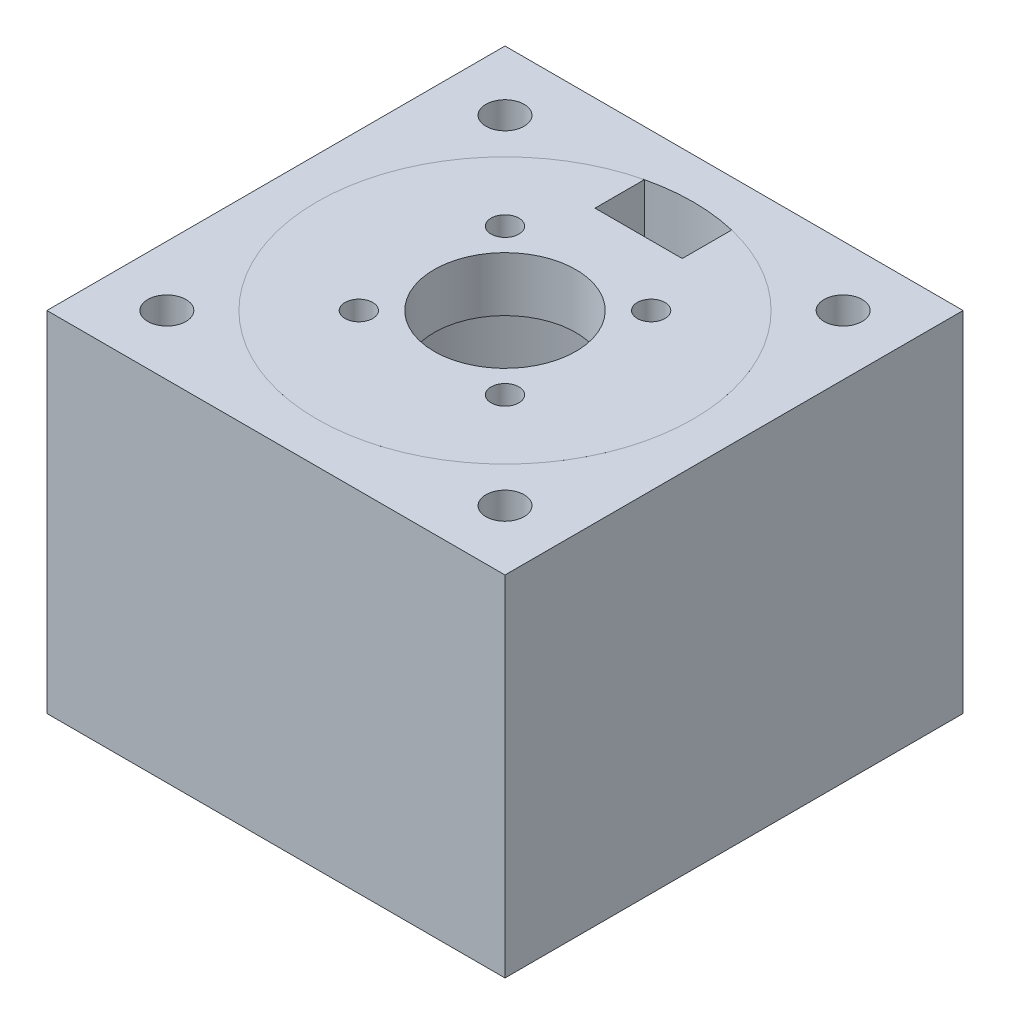
SolidWorks part; units mm, degrees
ref_plane "前视基准面" through (0, 0, 0) normal (0, 0, 1) x (1, 0, 0)
ref_plane "上视基准面" through (0, 0, 0) normal (0, 1, 0) x (1, 0, 0)
ref_plane "右视基准面" through (0, 0, 0) normal (1, 0, 0) x (0, 0, -1)
other "Configuration Table"
sketch "草图1" plane through (0, 0, 0) normal (0, 1, 0) x (1, 0, 0)
  line L0 (-42.7744, 0) -> (40.5419, 0) construction
  line L1 (0, 41.2812) -> (0, -32.3667) construction
  line L2 (-6.7, 41.2812) -> (-6.7, -32.3667) construction
  line L3 (6.7, 41.2812) -> (6.7, -32.3667) construction
  line L4 (-42.7744, -6.7) -> (40.5419, -6.7) construction
  line L5 (0, 41.2812) -> (0, -32.3667) construction
  line L6 (-42.7744, 6.7) -> (40.5419, 6.7) construction
  line L7 (0, 41.2812) -> (0, -32.3667) construction
  line L9 (-4, 22.25) -> (4, 22.25)
  line L10 (-4, 22.25) -> (-4, 12.25)
  line L11 (-4, 12.25) -> (4, 12.25)
  line L12 (4, 22.25) -> (4, 12.25)
  line L13 (-4, 22.25) -> (4, 12.25) construction
  line L14 (-4, 12.25) -> (4, 22.25) construction
  circle A0 centre (0, 0) radius 17.25
  circle A2 centre (-6.7, 6.7) radius 1.275
  circle A3 centre (6.7, 6.7) radius 1.275
  circle A4 centre (6.7, -6.7) radius 1.275
  circle A5 centre (-6.7, -6.7) radius 1.275
  circle A6 centre (0, 0) radius 6.5
  point P18 (0, 17.25)
  dimension "D1" = 34.5
  dimension "D6" = 2.55
  dimension "D9" = 13
  dimension "D2" = 6.7
  dimension "D3" = 6.7
  dimension "D7" = 10
  dimension "D8" = 8
  dimension "D4" = 6.7
  dimension "D5" = 6.7
extrude "凸台-拉伸1" add sketch "草图1" along normal blind 5 contours L10 A0 L12 L11 A3 A2 A4 A5
sketch "草图2" plane through (0, 0, 0) normal (0, -1, 0) x (1, 0, 0)
  line L0 (0, 60.9744) -> (0, -74.4705) construction
  line L1 (-76.6995, 0) -> (71.2326, 0) construction
  line L2 (-76.6995, -21) -> (71.2326, -21)
  line L3 (-76.6995, 21) -> (71.2326, 21)
  line L4 (-21, 60.9744) -> (-21, -74.4705)
  line L5 (21, 60.9744) -> (21, -74.4705)
  line L6 (-15.5, 60.9744) -> (-15.5, -74.4705) construction
  line L7 (15.5, 60.9744) -> (15.5, -74.4705) construction
  line L8 (-76.6995, -15.5) -> (71.2326, -15.5) construction
  line L9 (-76.6995, 15.5) -> (71.2326, 15.5) construction
  circle A0 centre (-15.5, 15.5) radius 1.75
  circle A1 centre (15.5, 15.5) radius 1.75
  circle A2 centre (15.5, -15.5) radius 1.75
  circle A3 centre (-15.5, -15.5) radius 1.75
  circle A4 centre (0, 0) radius 17.5
  arc A5 (4, -16.7798) -> (-4, -16.7798) centre (0, 0) ccw construction
  arc A6 (4, -16.7798) -> (-4, -16.7798) centre (0, 0) ccw
  line M10 (-4, -16.7798) -> (-4, -12.25)
  line M11 (-4, -12.25) -> (4, -12.25)
  line M12 (4, -12.25) -> (4, -16.7798)
  arc M13 (4, -16.7798) -> (-4, -16.7798) centre (0, 0) ccw
  dimension "D9" = 3.5
  dimension "D10" = 35
  dimension "D1" = 21
  dimension "D2" = 21
  dimension "D3" = 21
  dimension "D4" = 21
  dimension "D5" = 15.5
  dimension "D6" = 15.5
  dimension "D7" = 15.5
  dimension "D8" = 15.5
extrude "凸台-拉伸2" add sketch "草图2" along normal blind 27 separate body contours L5 L3 L4 L2 A1 A0 A2 A3 M10 M13 M12 M11
sketch "草图3" plane through (0, 0, 0) normal (0, 1, 0) x (1, 0, 0)
  line L0 (-21, -60.9744) -> (-21, 74.4705) construction
  line L1 (-76.6995, -21) -> (71.2326, -21) construction
  line L2 (21, -60.9744) -> (21, 74.4705) construction
  line L3 (-76.6995, 21) -> (71.2326, 21) construction
  line L4 (-21, -60.9744) -> (-21, 74.4705)
  line L5 (-76.6995, -21) -> (71.2326, -21)
  line L6 (21, -60.9744) -> (21, 74.4705)
  line L7 (-76.6995, 21) -> (71.2326, 21)
  circle A2 centre (0, 0) radius 17.25
  circle A3 centre (-15.5, -15.5) radius 1.75 construction
  circle A4 centre (15.5, -15.5) radius 1.75 construction
  circle A5 centre (15.5, 15.5) radius 1.75 construction
  circle A6 centre (-15.5, 15.5) radius 1.75 construction
  circle A7 centre (-15.5, -15.5) radius 1.75
  circle A8 centre (15.5, -15.5) radius 1.75
  circle A9 centre (15.5, 15.5) radius 1.75
  circle A10 centre (-15.5, 15.5) radius 1.75
  circle M2 centre (0, 0) radius 17.5
  circle M3 centre (15.5, -15.5) radius 1.75
  circle M4 centre (-15.5, -15.5) radius 1.75
  line M5 (21, -21) -> (21, 21)
  line M6 (21, 21) -> (-21, 21)
  line M7 (-21, 21) -> (-21, -21)
  line M8 (-21, -21) -> (21, -21)
  circle M9 centre (15.5, 15.5) radius 1.75
  circle M10 centre (-15.5, 15.5) radius 1.75
  dimension "D1" = 34.5
extrude "凸台-拉伸3" add sketch "草图3" along normal blind 5 contours A2 M2 | M8 M5 M6 M7 M3 M10 M9 M4 M2
